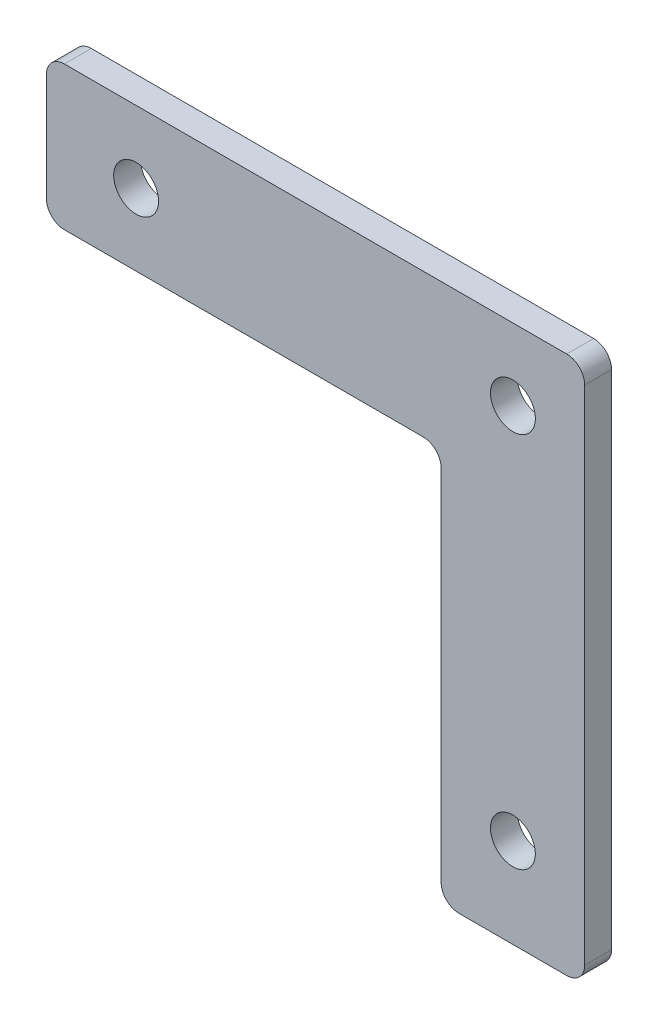
SolidWorks part; units mm, degrees
ref_plane "Płaszczyzna przednia" through (0, 0, 0) normal (0, 0, 1) x (1, 0, 0)
ref_plane "Płaszczyzna górna" through (0, 0, 0) normal (0, 1, 0) x (1, 0, 0)
ref_plane "Płaszczyzna prawa" through (0, 0, 0) normal (1, 0, 0) x (0, 0, -1)
sketch "Sketch1" plane through (0, 0, 0) normal (0, 0, 1) x (1, 0, 0)
  line L1 (0, 0) -> (44, 0)
  line L2 (0, 0) -> (0, 16)
  line L3 (0, 16) -> (60, 16)
  line L4 (60, -15.6568) -> (60, 16)
  line L5 (0, 0) -> (60, 16) construction
  line L8 (60, -15.6568) -> (60, -44)
  line L9 (60, -44) -> (44, -44)
  line L10 (44, 0) -> (44, -44)
  line L12 (60, -44) -> (44, 0) construction
  point P4 (30, 8)
  point P9 (45.6397, -4.5092)
  dimension "D1" = 60
  dimension "D2" = 16
  dimension "D3" = 60
  dimension "D4" = 16
extrude "Boss-Extrude1" add sketch "Sketch1" along normal blind 3
sketch "Sketch2" plane through (0, 0, 3) normal (0, 0, 1) x (1, 0, 0)
  line L0 (0, 0) -> (44, 0) construction
  line L1 (44, 0) -> (44, -44) construction
  line L3 (0, 16) -> (0, 0) construction
  line L7 (44, -44) -> (60, -44) construction
  circle A0 centre (10, 8) radius 2.5
  circle A2 centre (52, -34) radius 2.5
  dimension "D1" = 5
  dimension "D2" = 10
  dimension "D3" = 5
  dimension "D5" = 8
  dimension "D7" = 8
  dimension "D10" = 10
extrude "Cut-Extrude1" cut sketch "Sketch2" against normal blind 3
fillet "Fillet1" radius 2 6 edges at (44, -44, 1.5) (60, -44, 1.5) (44, 0, 1.5) (60, 16, 1.5) (0, 16, 1.5) (0, 0, 1.5)
hole_wizard "Ø5.0mm Dowel Hole1" positions "Sketch3" profile "Sketch4" hole size "Ø5.0" standard "ANSI Metric" end condition up to next
sketch "Sketch3" plane through (0, 0, 0) normal (0, 0, -1) x (-1, 0, 0)
  line L0 (-60, -42) -> (-60, 14) construction
  line L1 (-58, 16) -> (-2, 16) construction
  point P0 (-52, 8)
  dimension "D1" = 8
  dimension "D2" = 8
sketch "Sketch4" plane through (52, 8, 0) normal (1, 0, 0) x (0, 1, 0)
  line L0 (0, 0) -> (0, 3)
  line L1 (0, 3) -> (2.5, 3)
  line L2 (2.5, 3) -> (2.5, 0)
  line L5 (2.5, 0) -> (0, 0)
  line L11 (0, -6.35) -> (0, 107.95) construction
  dimension "Thru Hole Dia." = 5
  dimension "Thru Hole Depth" = 3
hole_wizard "Ø4.0mm Dowel Hole1" positions "Sketch5" profile "Sketch6" hole size "Ø4.0" standard "ANSI Metric"
sketch "Sketch5" plane through (0, 0, 3) normal (0, 0, 1) x (1, 0, 0)
  line L0 (32, -18) -> (32, 10) construction
  line L2 (30, 12) -> (2, 12) construction
  point P0 (26, 6)
  dimension "D1" = 6
  dimension "D2" = 6
sketch "Sketch6" plane through (26, 6, 3) normal (1, 0, 0) x (0, -1, 0)
  line L0 (0, 0) -> (0, 3)
  line L1 (0, 3) -> (2, 3)
  line L2 (2, 3) -> (2, 0)
  line L5 (2, 0) -> (0, 0)
  line L11 (0, -6.35) -> (0, 107.95) construction
  dimension "Thru Hole Dia." = 4
  dimension "Thru Hole Depth" = 3
